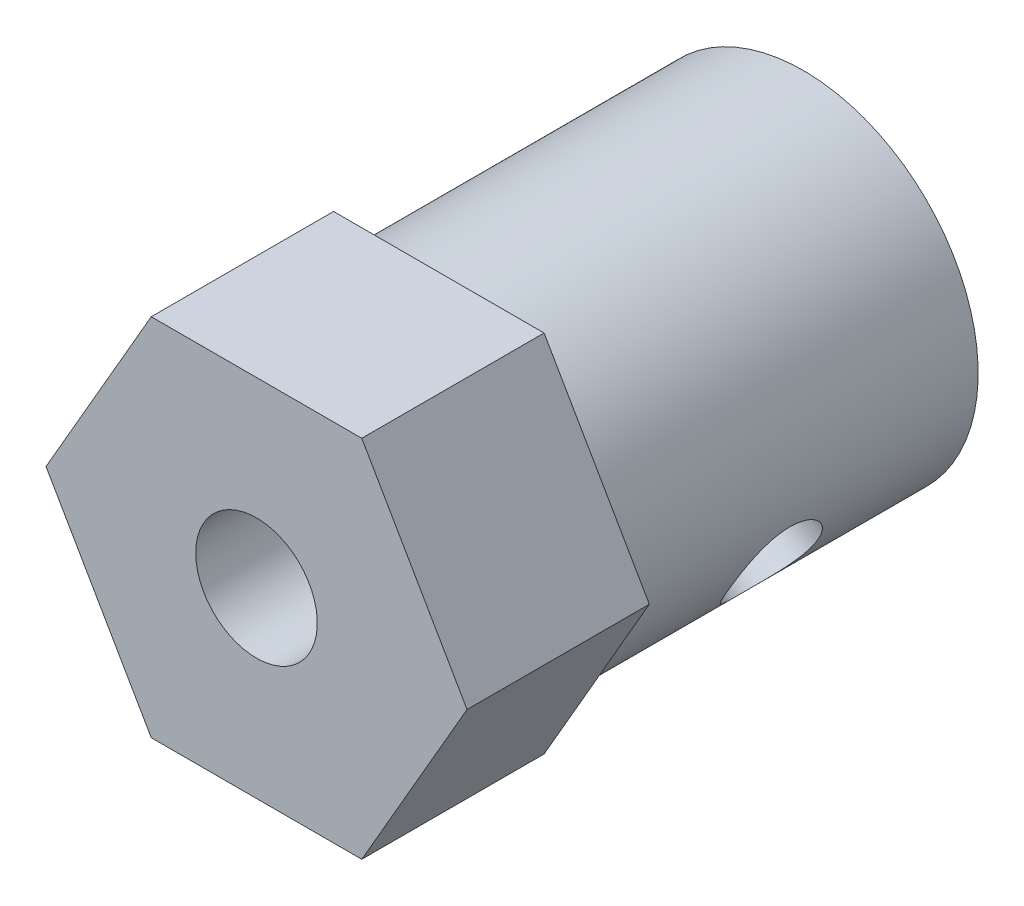
SolidWorks part; units mm, degrees
material "Brass"
ref_plane "Front Plane" through (0, 0, 0) normal (1, 0, 0) x (0, 1, 0)
ref_plane "Top Plane" through (0, 0, 0) normal (0, 0, 1) x (0, 1, 0)
ref_plane "Right Plane" through (0, 0, 0) normal (0, 1, 0) x (-1, 0, 0)
sketch "Sketch1" plane through (0, 0, 0) normal (0, 0, 1) x (0, 1, 0)
  line L1 (0, 6.9282) -> (-6, 3.4641)
  line L2 (-6, 3.4641) -> (-6, -3.4641)
  line L3 (-6, -3.4641) -> (0, -6.9282)
  line L4 (0, -6.9282) -> (6, -3.4641)
  line L5 (6, -3.4641) -> (6, 3.4641)
  line L6 (6, 3.4641) -> (0, 6.9282)
  circle A0 centre (0, 0) radius 6 construction
  dimension "D1" = 12
extrude "Boss-Extrude1" add sketch "Sketch1" along normal blind 6
sketch "Sketch2" plane through (0, 0, 0) normal (0, 0, -1) x (1, 0, 0)
  circle A0 centre (0, 0) radius 5.75
  dimension "D1" = 11.5
extrude "Boss-Extrude2" add sketch "Sketch2" along normal blind 12
sketch "Sketch4" plane through (0, 0, -12) normal (0, 0, -1) x (1, 0, 0)
  circle A0 centre (0, 0) radius 2
  dimension "D1" = 4
extrude "Cut-Extrude2" cut sketch "Sketch4" against normal through all
ref_plane "Plane1" through (5.1962, -3, 0) normal (0.866, -0.5, 0) x (0, 0, -1)
sketch "Sketch5" plane through (5.1962, -3, 0) normal (0.866, -0.5, 0) x (0.5, 0.866, 0)
  line L0 (-3.4641, 0) -> (3.4641, 0) construction
  circle A0 centre (0, -6) radius 1.5
  dimension "D2" = 3
  dimension "D1" = 6
extrude "Cut-Extrude3" cut sketch "Sketch5" against normal blind 6 contours A0
